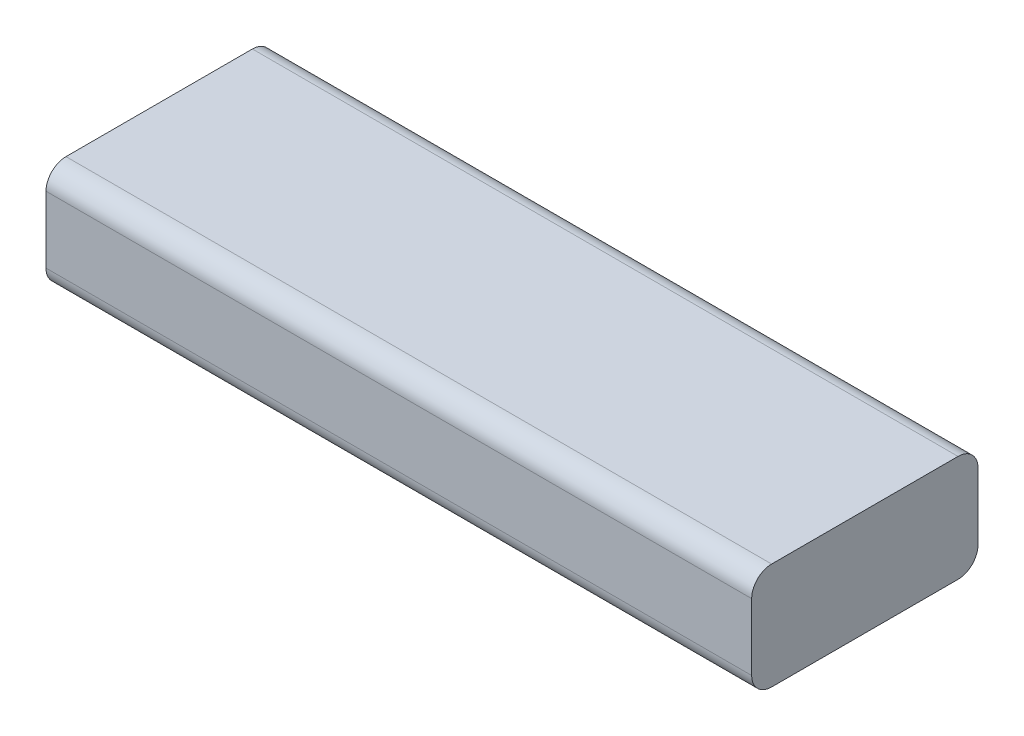
SolidWorks part; units mm, degrees
ref_plane "Front Plane" through (0, 0, 0) normal (0, 0, 1) x (1, 0, 0)
ref_plane "Top Plane" through (0, 0, 0) normal (0, 1, 0) x (1, 0, 0)
ref_plane "Right Plane" through (0, 0, 0) normal (1, 0, 0) x (0, 0, -1)
sketch "Sketch1" plane through (0, 0, 0) normal (0, 1, 0) x (1, 0, 0)
  line L1 (0, 0) -> (106, 0)
  line L2 (0, 0) -> (0, 34)
  line L3 (0, 34) -> (106, 34)
  line L4 (106, 0) -> (106, 34)
  dimension "D1" = 106
  dimension "D2" = 34
extrude "Boss-Extrude1" add sketch "Sketch1" along normal blind 16
fillet "Fillet2" radius 3 4 edges at (53, 0, -34) (53, 16, -34) (53, 0, 0) (53, 16, 0)
